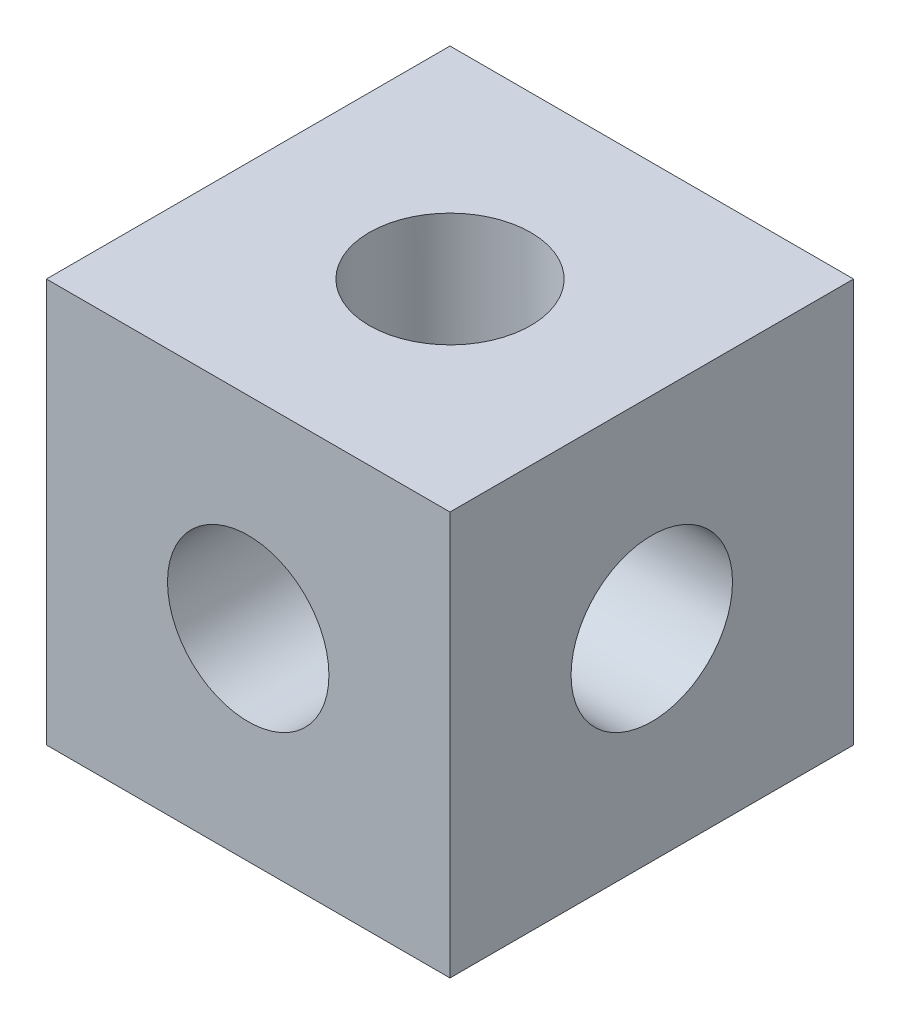
SolidWorks part; units mm, degrees
material "1060 合金"
ref_plane "前视基准面" through (0, 0, 0) normal (0, 0, 1) x (1, 0, 0)
ref_plane "上视基准面" through (0, 0, 0) normal (0, 1, 0) x (1, 0, 0)
ref_plane "右视基准面" through (0, 0, 0) normal (1, 0, 0) x (0, 0, -1)
other "Configuration Table"
sketch "草图1" plane through (0, 0, 0) normal (0, 1, 0) x (1, 0, 0)
  line L1 (-5, -5) -> (5, -5)
  line L2 (-5, -5) -> (-5, 5)
  line L3 (-5, 5) -> (5, 5)
  line L4 (5, -5) -> (5, 5)
  line L5 (-5, -5) -> (5, 5) construction
  line L6 (-5, 5) -> (5, -5) construction
  circle A0 centre (0, 0) radius 2
  point P0 (0, 0)
  dimension "D3" = 4
  dimension "D1" = 10
  dimension "D2" = 10
extrude "凸台-拉伸1" add sketch "草图1" along normal blind 10
sketch "草图2" plane through (0, 0, 5) normal (0, 0, 1) x (1, 0, 0)
  line L0 (5, 10) -> (5, 0) construction
  line L1 (-5, 0) -> (5, 0) construction
  circle A0 centre (0, 5) radius 2
  dimension "D1" = 4
  dimension "D2" = 5
  dimension "D3" = 5
extrude "切除-拉伸1" cut sketch "草图2" against normal blind 10
sketch "草图3" plane through (5, 0, 0) normal (1, 0, 0) x (0, 0, -1)
  line L0 (5, 10) -> (5, 0) construction
  line L1 (-5, 0) -> (5, 0) construction
  circle A0 centre (0, 5) radius 2
  dimension "D1" = 4
  dimension "D2" = 5
  dimension "5" = 5
extrude "切除-拉伸2" cut sketch "草图3" against normal blind 10
